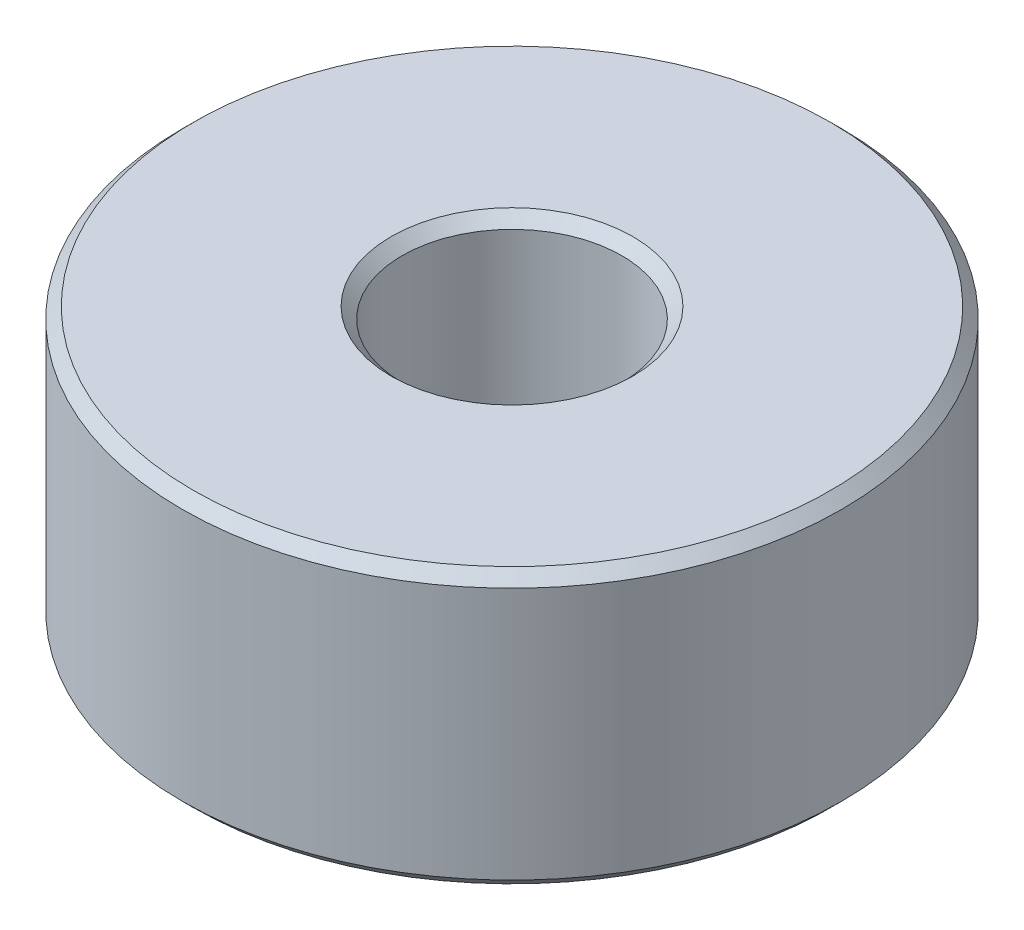
SolidWorks part; units mm, degrees
ref_plane "Front Plane" through (0, 0, 0) normal (0, 0, 1) x (1, 0, 0)
ref_plane "Top Plane" through (0, 0, 0) normal (0, 1, 0) x (1, 0, 0)
ref_plane "Right Plane" through (0, 0, 0) normal (1, 0, 0) x (0, 0, -1)
sketch "Sketch2" plane through (0, 0, 0) normal (0, 1, 0) x (1, 0, 0)
  circle A0 centre (0, 0) radius 3
  circle A1 centre (0, 0) radius 1
  dimension "D1" = 6
  dimension "D2" = 2
extrude "Boss-Extrude1" add sketch "Sketch2" along normal blind 2.5
chamfer "Chamfer1" distance 0.1 angle 45 4 edges at (0, 0, 1) (0, 0, 3) (0, 2.5, 1) (0, 2.5, 3)
